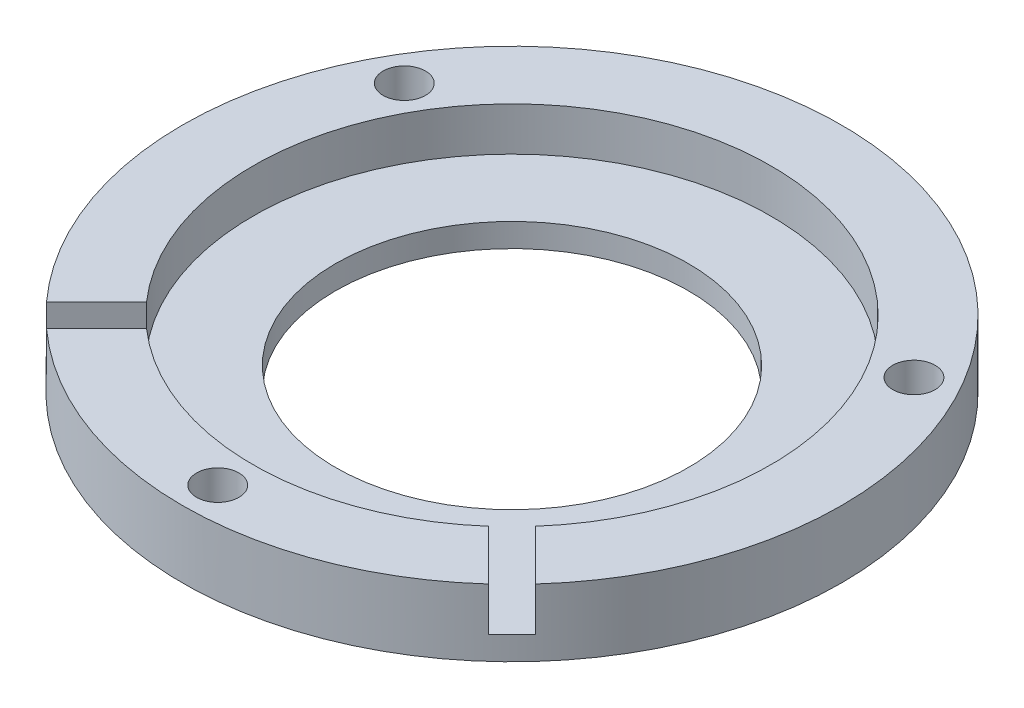
SolidWorks part; units mm, degrees
ref_plane "Front" through (0, 0, 0) normal (0, 0, 1) x (1, 0, 0)
ref_plane "Top" through (0, 0, 0) normal (0, 1, 0) x (1, 0, 0)
ref_plane "Right" through (0, 0, 0) normal (1, 0, 0) x (0, 0, -1)
sketch "Sketch1" plane through (0, 0, 0) normal (0, 0, 1) x (1, 0, 0)
  line L0 (0, 0) -> (14, 0)
  line L1 (14, 0) -> (14, 2.85)
  line L2 (14, 2.85) -> (11, 2.85)
  line L3 (11, 2.85) -> (11, 1)
  line L4 (11, 1) -> (0, 1)
  line L5 (0, 1) -> (0, 0)
  line L6 (7.5, 1) -> (7.5, 0)
  dimension "D1" = 11
  dimension "D2" = 3
  dimension "D3" = 1.85
  dimension "D4" = 1
  dimension "D5" = 7.5
revolve "Revolve1" add sketch "Sketch1" angle 360 about L5
sketch "Sketch2" plane through (0, 2.85, 0) normal (0, 1, 0) x (1, 0, 0)
  line L0 (0, 0) -> (0, -14) construction
  line L1 (0, 0) -> (-9.8995, -9.8995)
  line L2 (-10.3945, -9.4045) -> (-9.4045, -10.3945)
  line L3 (-0.495, 0.495) -> (0.495, -0.495)
  line L4 (-10.3945, -9.4045) -> (-0.495, 0.495)
  line L5 (-9.4045, -10.3945) -> (0.495, -0.495)
  line L6 (10.3945, -9.4045) -> (0.495, 0.495)
  line L7 (-0.495, -0.495) -> (0.495, 0.495)
  line L8 (9.4045, -10.3945) -> (-0.495, -0.495)
  line L9 (9.4045, -10.3945) -> (10.3945, -9.4045)
  line L10 (0, 0) -> (0.495, -0.495) construction
  line L11 (0, 0) -> (0.495, 0.495) construction
  circle A0 centre (0, 0) radius 14 construction
  point P10 (-9.8995, -9.8995)
  point P15 (0, 0)
  circle M7 centre (0, 0) radius 11
  circle M8 centre (0, 0) radius 14
  dimension "D1" = 45
  dimension "D2" = 1.4
  dimension "D4" = 90
  dimension "D3" = 2
extrude "Cut-Extrude1" cut sketch "Sketch2" against normal up to surface (1.85 mm away) contours L5 L1 M8 M7 | L4 L1 M8 M7 | L8 L6 M8 M7 up to face at (-7.5, 1, 0)
sketch "Sketch4" plane through (0, 2.85, 0) normal (0, 1, 0) x (1, 0, 0)
  line L0 (0, 0) -> (0, -12.5) construction
  circle A0 centre (0, -12.5) radius 0.9
  circle A1 centre (-10.8253, 6.25) radius 0.9
  circle A2 centre (10.8253, 6.25) radius 0.9
  dimension "D2" = 1.8
  dimension "D1" = 12.5
  dimension "D3" = 3
extrude "Cut-Extrude2" cut sketch "Sketch4" against normal through all contours A1 | A2 | A0
